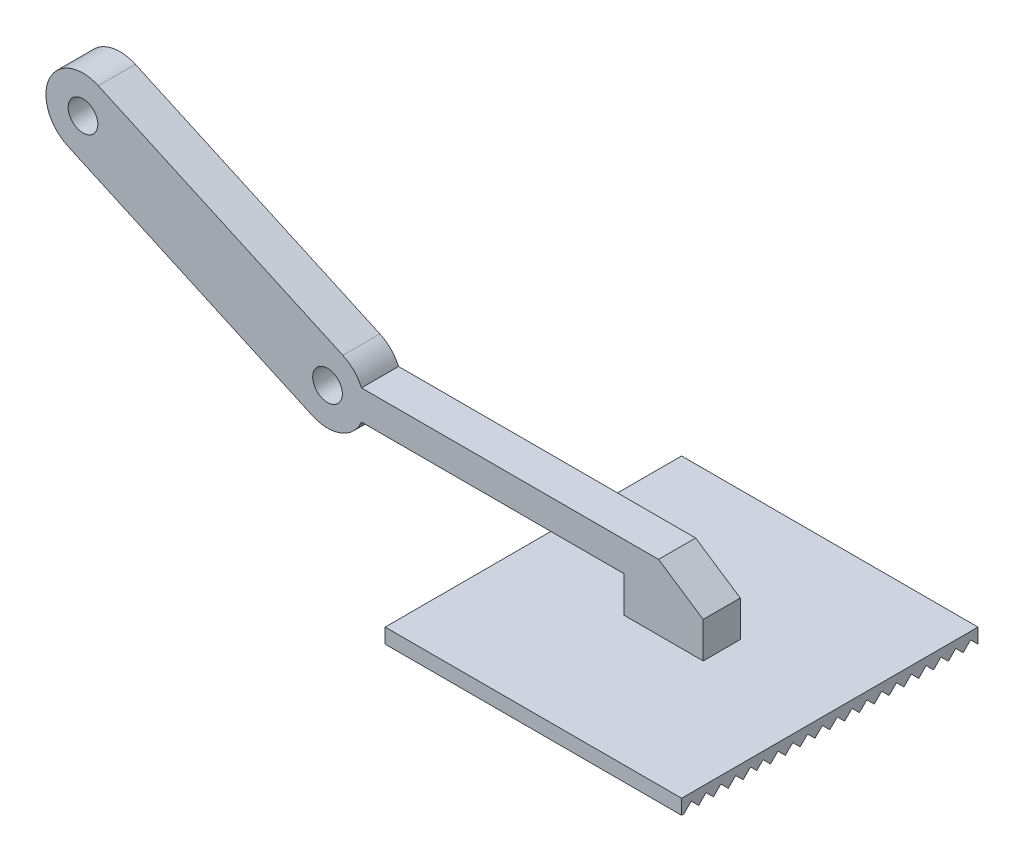
SolidWorks part; units mm, degrees
ref_plane "前视基准面" through (0, 0, 0) normal (0, 0, 1) x (1, 0, 0)
ref_plane "上视基准面" through (0, 0, 0) normal (0, 1, 0) x (1, 0, 0)
ref_plane "右视基准面" through (0, 0, 0) normal (1, 0, 0) x (0, 0, -1)
sketch "草图1" plane through (0, 0, 0) normal (0, 0, 1) x (1, 0, 0)
  line L0 (0, 0) -> (33, -15) construction
  line L1 (2.069, 4.5518) -> (35.069, -10.4482)
  line L2 (-2.069, -4.5518) -> (30.931, -19.5518)
  line L3 (33, -15) -> (73, -15) construction
  line L4 (37.5826, -13) -> (73, -13)
  line L5 (37.5826, -17) -> (73, -17)
  line L6 (73, -17) -> (73, -21.8568)
  line L7 (73, -21.8568) -> (83.6935, -21.8568)
  line L8 (83.6935, -21.8568) -> (83.6935, -17)
  line L9 (83.6935, -17) -> (77.6694, -13)
  line L10 (77.6694, -13) -> (73, -13)
  arc A0 (2.069, 4.5518) -> (-2.069, -4.5518) centre (0, 0) ccw
  arc A1 (30.931, -19.5518) -> (37.5826, -17) centre (33, -15) ccw
  arc A4 (37.5826, -13) -> (35.069, -10.4482) centre (33, -15) ccw
  circle A5 centre (0, 0) radius 2
  circle A6 centre (33, -15) radius 2
  point P3 (16.5, -7.5)
  point P10 (53, -15)
  dimension "D1" = 33
  dimension "D2" = 15
extrude "凸台-拉伸1" add sketch "草图1" along normal mid plane 5
sketch "草图2" plane through (0, -21.8568, 0) normal (0, -1, 0) x (1, 0, 0)
  line L0 (14.7713, 0) -> (-14.7713, 0) construction
  line L1 (58.2757, 20) -> (98.2757, 20)
  line L2 (58.2757, 20) -> (58.2757, -20)
  line L3 (58.2757, -20) -> (98.2757, -20)
  line L4 (98.2757, 20) -> (98.2757, -20)
  line L5 (58.2757, 20) -> (98.2757, -20) construction
  line L6 (58.2757, -20) -> (98.2757, 20) construction
  point P0 (78.2757, 0)
  dimension "D1" = 40
  dimension "D2" = 40
extrude "凸台-拉伸2" add sketch "草图2" along normal blind 2
sketch "草图4" plane through (58.2757, 0, 0) normal (-1, 0, 0) x (0, 0, 1)
  line L0 (-20, -23.8568) -> (20, -23.8568)
  line L1 (-20, -23.8568) -> (-19, -22.8568)
  line L2 (-19, -22.8568) -> (-18, -23.8568)
  line L3 (20, -23.8568) -> (-20, -23.8568) construction
  line L4 (-18, -23.8568) -> (-17, -22.8568)
  line L5 (-17, -22.8568) -> (-16, -23.8568)
  line L6 (-16, -23.8568) -> (-15, -22.8568)
  line L7 (-15, -22.8568) -> (-14, -23.8568)
  line L8 (-14, -23.8568) -> (-13, -22.8568)
  line L9 (-13, -22.8568) -> (-12, -23.8568)
  line L10 (-12, -23.8568) -> (-11, -22.8568)
  line L11 (-11, -22.8568) -> (-10, -23.8568)
  line L12 (-10, -23.8568) -> (-9, -22.8568)
  line L13 (-9, -22.8568) -> (-8, -23.8568)
  line L14 (-8, -23.8568) -> (-7, -22.8568)
  line L15 (-7, -22.8568) -> (-6, -23.8568)
  line L16 (-6, -23.8568) -> (-5, -22.8568)
  line L17 (-5, -22.8568) -> (-4, -23.8568)
  line L18 (-4, -23.8568) -> (-3, -22.8568)
  line L19 (-3, -22.8568) -> (-2, -23.8568)
  line L20 (-2, -23.8568) -> (-1, -22.8568)
  line L21 (-1, -22.8568) -> (0, -23.8568)
  line L22 (0, -23.8568) -> (1, -22.8568)
  line L23 (1, -22.8568) -> (2, -23.8568)
  line L24 (2, -23.8568) -> (3, -22.8568)
  line L25 (3, -22.8568) -> (4, -23.8568)
  line L26 (4, -23.8568) -> (5, -22.8568)
  line L27 (5, -22.8568) -> (6, -23.8568)
  line L28 (6, -23.8568) -> (7, -22.8568)
  line L29 (7, -22.8568) -> (8, -23.8568)
  line L30 (8, -23.8568) -> (9, -22.8568)
  line L31 (9, -22.8568) -> (9.848, -23.7048)
  line L32 (9.848, -23.7048) -> (10.6959, -22.8568)
  line L33 (10.6959, -22.8568) -> (11.6959, -23.8568)
  line L34 (11.6959, -23.8568) -> (12.6959, -22.8568)
  line L35 (12.6959, -22.8568) -> (13.6959, -23.8568)
  line L36 (13.6959, -23.8568) -> (14.6959, -22.8568)
  line L37 (14.6959, -22.8568) -> (15.6959, -23.8568)
  line L38 (15.6959, -23.8568) -> (16.6959, -22.8568)
  line L39 (16.6959, -22.8568) -> (17.6959, -23.8568)
  line L40 (17.6959, -23.8568) -> (18.6959, -22.8568)
  line L41 (18.6959, -22.8568) -> (19.6959, -23.8568)
  line L42 (19.6959, -23.8568) -> (-20, -23.8568)
  line M5 (-20, -23.8568) -> (20, -23.8568)
extrude "切除-拉伸1" cut sketch "草图4" against normal blind 40 contours L2 L1 M5 | L5 L4 L0 | L7 L6 M5 | L9 L8 L0 | L11 L10 M5 | L13 L12 L0 | L15 L14 M5 | L17 L16 L0 | L19 L18 M5 | L21 L20 L0 | L23 L22 M5 | L25 L24 L0 | L27 L26 M5 | L29 L28 L0 | L33 L32 L31 L30 M5 | L35 L34 L0 | L41 L40 M5 | L39 L38 L0 | L37 L36 M5
